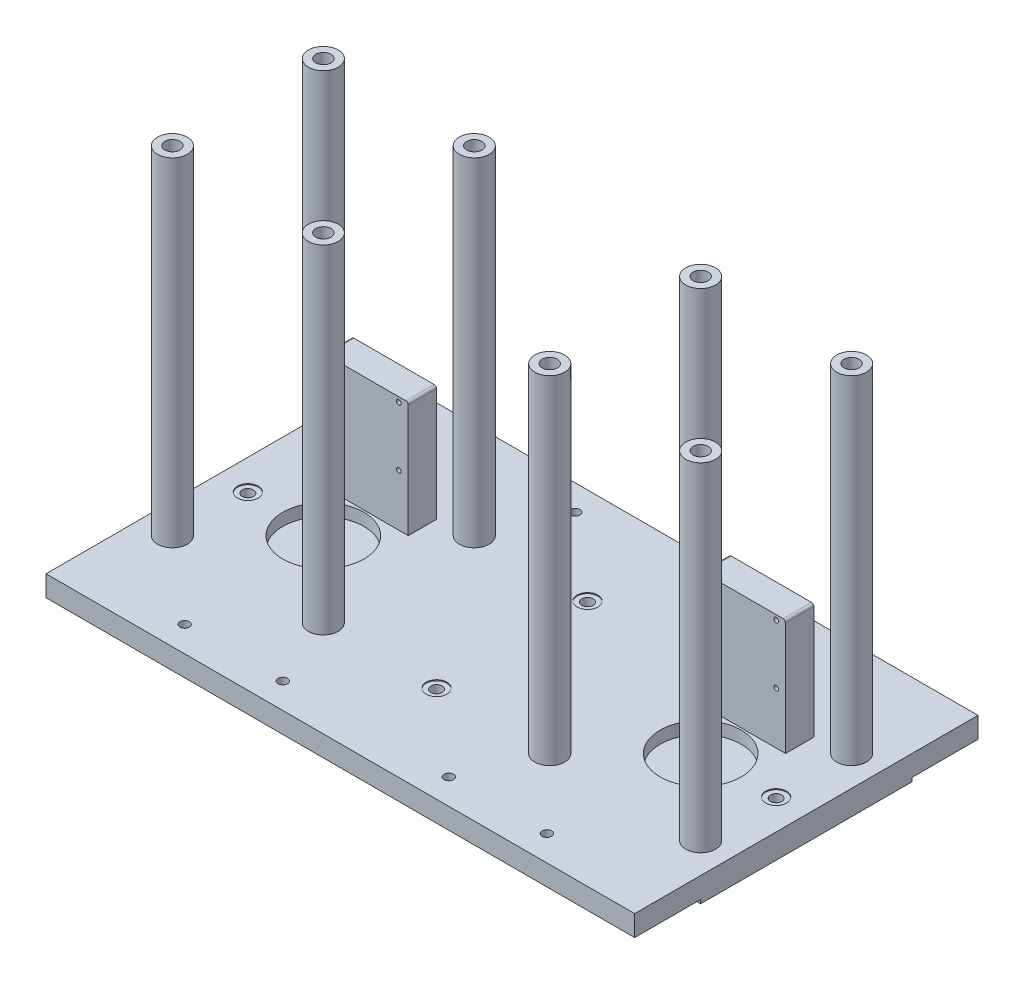
SolidWorks part; units mm, degrees
material "1.4511 (X3CrNb17)"
ref_plane "前视基准面" through (0, 0, 0) normal (0, 0, 1) x (1, 0, 0)
ref_plane "上视基准面" through (0, 0, 0) normal (0, 1, 0) x (1, 0, 0)
ref_plane "右视基准面" through (0, 0, 0) normal (1, 0, 0) x (0, 0, -1)
sketch "草图1" plane through (0, 0, 0) normal (0, 1, 0) x (1, 0, 0)
  line L1 (-156, 56) -> (156, 56)
  line L2 (-156, 56) -> (-156, -56)
  line L3 (-156, -56) -> (156, -56)
  line L4 (156, 56) -> (156, -56)
  line L5 (-156, 56) -> (156, -56) construction
  line L6 (-156, -56) -> (156, 56) construction
  point P0 (0, 0)
  dimension "D1" = 312
  dimension "D2" = 112
extrude "凸台-拉伸1" add sketch "草图1" along normal blind 2
sketch "草图2" plane through (0, 2, 0) normal (0, 1, 0) x (1, 0, 0)
  line L1 (-156, 91) -> (156, 91)
  line L2 (-156, 91) -> (-156, -91)
  line L3 (-156, -91) -> (156, -91)
  line L4 (156, 91) -> (156, -91)
  line L5 (-156, 91) -> (156, -91) construction
  line L6 (-156, -91) -> (156, 91) construction
  point P0 (0, 0)
  dimension "D1" = 182
  dimension "D2" = 312
extrude "凸台-拉伸2" add sketch "草图2" along normal blind 11
sketch "草图3" plane through (0, 13, 0) normal (0, 1, 0) x (1, 0, 0)
  line L1 (-60, 40) -> (60, 40) construction
  line L2 (-60, 40) -> (-60, -40) construction
  line L3 (-60, -40) -> (60, -40) construction
  line L4 (60, 40) -> (60, -40) construction
  line L5 (-60, 40) -> (60, -40) construction
  line L6 (-60, -40) -> (60, 40) construction
  line L7 (-140, 40) -> (140, 40) construction
  line L8 (-140, 40) -> (-140, -40) construction
  line L9 (-140, -40) -> (140, -40) construction
  line L10 (140, 40) -> (140, -40) construction
  line L11 (-140, 40) -> (140, -40) construction
  line L12 (-140, -40) -> (140, 40) construction
  circle A0 centre (-60, 40) radius 7.9
  circle A1 centre (60, 40) radius 7.9
  circle A2 centre (-60, -40) radius 7.9
  circle A3 centre (60, -40) radius 7.9
  circle A4 centre (-140, -40) radius 7.9
  circle A5 centre (-140, 40) radius 7.9
  circle A6 centre (140, 40) radius 7.9
  circle A7 centre (140, -40) radius 7.9
  point P0 (0, 0)
  point P10 (0, 0)
  dimension "D3" = 15.8
  dimension "D4" = 15.8
  dimension "D5" = 15.8
  dimension "D6" = 15.8
  dimension "D9" = 15.8
  dimension "D10" = 15.8
  dimension "D11" = 15.8
  dimension "D12" = 15.8
  dimension "D1" = 120
  dimension "D2" = 80
  dimension "D7" = 80
  dimension "D8" = 280
extrude "凸台-拉伸3" add sketch "草图3" along normal blind 179 separate body
sketch "草图4" plane through (0, 13, 0) normal (0, 1, 0) x (1, 0, 0)
  line L0 (-100, 0) -> (100, 0) construction
  circle A0 centre (-100, 0) radius 21.5
  circle A1 centre (100, 0) radius 21.5
  point P4 (0, 0)
  dimension "D2" = 43
  dimension "D3" = 43
  dimension "D1" = 200
extrude "切除-拉伸2" cut sketch "草图4" against normal blind 6.5
sketch "草图5" plane through (0, 13, 0) normal (0, 1, 0) x (1, 0, 0)
  line L0 (-156, -91) -> (156, -91) construction
  line L1 (-96, 77.5) -> (-44, 77.5) construction
  line L2 (-96, 77.5) -> (-96, -77.5) construction
  line L3 (-96, -77.5) -> (-44, -77.5) construction
  line L4 (-44, 77.5) -> (-44, -77.5) construction
  line L5 (-156, 91) -> (-156, -91) construction
  dimension "D1" = 52
  dimension "D2" = 155
  dimension "D3" = 13.5
  dimension "D4" = 60
hole_wizard "M5 螺纹孔的螺纹孔钻头1" positions "草图6" profile "草图7" hole size "M5" standard "GB"
sketch "草图6" plane through (0, 13, 0) normal (0, 1, 0) x (1, 0, 0)
  point P0 (-96, 77.5)
  point P3 (-44, 77.5)
  point P6 (-44, -77.5)
  point P9 (-96, -77.5)
sketch "草图7" plane through (-96, 13, -77.5) normal (1, 0, 0) x (0, 0, 1)
  line L0 (0, 0) -> (0, 11.0022)
  line L1 (0, 11.0022) -> (2.5, 9.5)
  line L2 (2.5, 9.5) -> (2.5, 0)
  line L5 (2.5, 0) -> (0, 0)
  line L10 (0, 11.0022) -> (-2.5, 9.5) construction
  line L11 (0, -6.35) -> (0, 107.95) construction
  dimension "孔直径" = 5
  dimension "孔深度" = 9.5
  dimension "导头角度" = 118
sketch "草图22" plane through (0, 13, 0) normal (0, 1, 0) x (1, 0, 0)
  line L0 (-156, -91) -> (156, -91) construction
  line L1 (-140, 40) -> (140, 40) construction
  line L2 (-140, 40) -> (-140, -40) construction
  line L3 (-140, -40) -> (140, -40) construction
  line L4 (140, 40) -> (140, -40) construction
  line L5 (-156, 91) -> (-156, -91) construction
  line L6 (0, 110.7954) -> (0, -130.8244) construction
  line L7 (-175.9692, 0) -> (187.4143, 0) construction
  dimension "D1" = 280
  dimension "D2" = 80
  dimension "D3" = 51
  dimension "D4" = 16
hole_wizard "M5 六角头螺栓的柱形沉头孔1" positions "草图25" profile "草图26" counterbore size "M5" standard "GB" end condition through all
sketch "草图25" plane through (0, 13, 0) normal (0, 1, 0) x (1, 0, 0)
  line L0 (-140, 40) -> (-140, -40) construction
  line L1 (-140, 40) -> (140, 40) construction
  line L2 (-140, -40) -> (140, -40) construction
  line L3 (140, 40) -> (140, -40) construction
  point P0 (-140, 0)
  point P4 (0, 40)
  point P8 (0, -40)
  point P12 (140, 0)
sketch "草图26" plane through (-140, 13, 0) normal (1, 0, 0) x (0, 0, 1)
  line L0 (0, 0) -> (0, 13)
  line L1 (0, 13) -> (3, 13)
  line L3 (3, 13) -> (3, 0.5)
  line L4 (3, 0.5) -> (5.5, 0.5)
  line L5 (5.5, 0.5) -> (5.5, 0)
  line L7 (5.5, 0) -> (0, 0)
  line L11 (0, -6.35) -> (0, 107.95) construction
  dimension "通孔孔直径" = 6
  dimension "通孔孔深度" = 13
  dimension "柱形沉头孔直径" = 11
  dimension "柱形沉头孔深度" = 0.5
hole_wizard "M8 螺纹孔的螺纹孔钻头1" positions "草图27" profile "草图28" hole size "M8" standard "GB"
sketch "草图27" plane through (0, 192, 0) normal (0, 1, 0) x (1, 0, 0)
  point P0 (-140, 40)
  point P3 (-60, 40)
  point P6 (-60, -40)
  point P9 (-140, -40)
  point P12 (60, 40)
  point P15 (140, 40)
  point P18 (140, -40)
  point P21 (60, -40)
sketch "草图28" plane through (-140, 192, -40) normal (1, 0, 0) x (0, 0, 1)
  line L0 (0, 0) -> (0, 15.4034)
  line L1 (0, 15.4034) -> (4, 13)
  line L2 (4, 13) -> (4, 0)
  line L5 (4, 0) -> (0, 0)
  line L10 (0, 15.4034) -> (-4, 13) construction
  line L11 (0, -6.35) -> (0, 107.95) construction
  dimension "孔直径" = 8
  dimension "孔深度" = 13
  dimension "导头角度" = 118
sketch "草图31" plane through (0, 13, 0) normal (0, 1, 0) x (1, 0, 0)
  line L1 (-122.5, 37.5) -> (-77.5, 37.5)
  line L2 (-122.5, 37.5) -> (-122.5, 22.5)
  line L3 (-122.5, 22.5) -> (-77.5, 22.5)
  line L4 (-77.5, 37.5) -> (-77.5, 22.5)
  circle A0 centre (-100, 0) radius 21.5 construction
  dimension "D1" = 45
  dimension "D2" = 15
  dimension "D3" = 22.5
  dimension "D4" = 22.5
extrude "凸台-拉伸4" add sketch "草图31" along normal blind 61.25
sketch "草图32" plane through (0, 0, -22.5) normal (0, 0, 1) x (1, 0, 0)
  line L0 (-122.5, 74.25) -> (-77.5, 74.25) construction
  line L1 (-117.5, 71.75) -> (-82.5, 71.75) construction
  line L2 (-117.5, 71.75) -> (-117.5, 40.5) construction
  line L3 (-117.5, 40.5) -> (-82.5, 40.5) construction
  line L4 (-82.5, 71.75) -> (-82.5, 40.5) construction
  line L5 (-77.5, 74.25) -> (-77.5, 13) construction
  circle A0 centre (-117.5, 71.75) radius 1.25
  circle A1 centre (-82.5, 71.75) radius 1.25
  circle A2 centre (-82.5, 40.5) radius 1.25
  circle A3 centre (-117.5, 40.5) radius 1.25
  dimension "D5" = 2.5
  dimension "D6" = 2.5
  dimension "D7" = 2.5
  dimension "D8" = 2.5
  dimension "D1" = 35
  dimension "D2" = 31.25
  dimension "D3" = 2.5
  dimension "D4" = 5
extrude "切除-拉伸3" cut sketch "草图32" against normal through all
fillet "圆角1" radius 1.25 2 edges at (-77.5, 74.25, -30) (-122.5, 74.25, -30)
mirror "镜向1" about plane through (0, 0, 0) normal (1, 0, 0) of "圆角1", "切除-拉伸3", "凸台-拉伸4", "M5 螺纹孔的螺纹孔钻头1"
